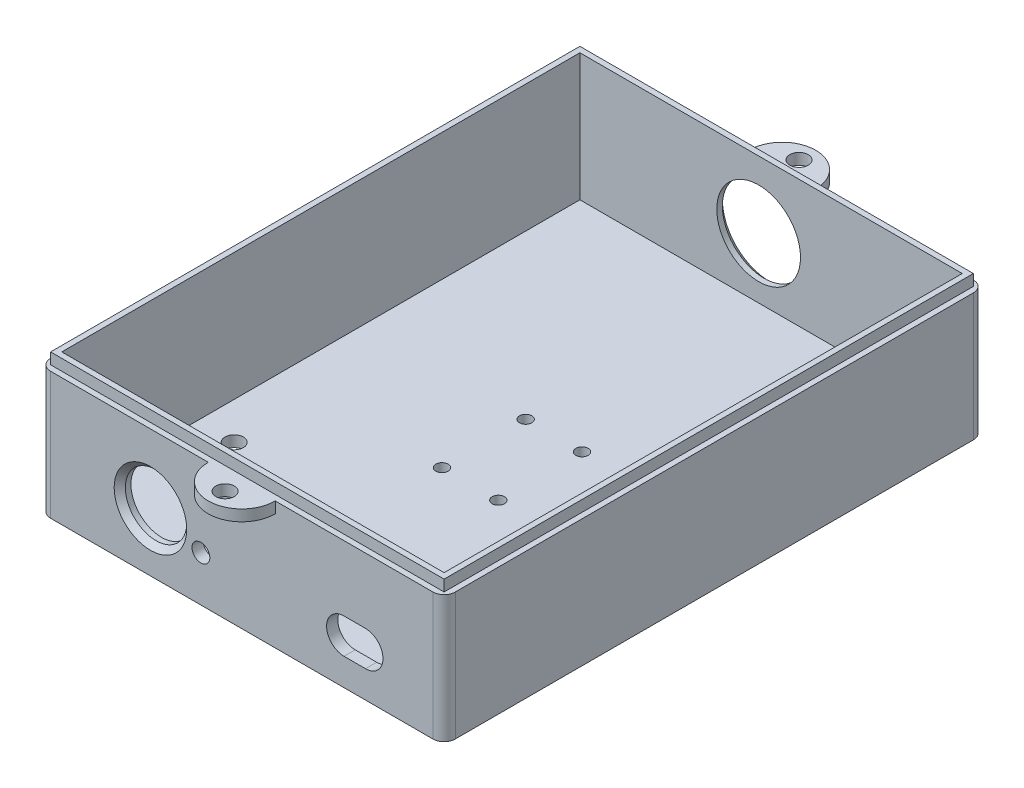
SolidWorks part; units mm, degrees
ref_plane "Front Plane" through (0, 0, 0) normal (1, 0, 0) x (0, 1, 0)
ref_plane "Top Plane" through (0, 0, 0) normal (0, 0, 1) x (0, 1, 0)
ref_plane "Right Plane" through (0, 0, 0) normal (0, 1, 0) x (-1, 0, 0)
sketch "Sketch1" plane through (0, 0, 0) normal (0, 1, 0) x (1, 0, 0)
  line L0 (80.8703, 33.3957) -> (153.3703, 33.3957)
  line L1 (153.3703, 33.3957) -> (153.3703, -63.4327)
  line L2 (153.3703, -63.4327) -> (80.8703, -63.4327)
  line L3 (80.8703, -63.4327) -> (80.8703, 33.3957)
extrude "Boss-Extrude1" add sketch "Sketch1" along normal blind 18 and the other way offset from surface (12.8155 mm away) 0.5 contours L0 L1 L2 L3
shell "Shell1" thickness 2
sketch "Sketch2" plane through (0, 0, -33.3957) normal (0, 0, -1) x (-1, 0, 0)
  line L2 (-80.8703, -12.8155) -> (-153.3703, -12.8155) construction
  line L3 (-153.3703, -12.8155) -> (-153.3703, 18) construction
  circle A0 centre (-114.8937, -0.0005) radius 7.5
  dimension "D1" = 15
  dimension "D2" = 12.815
  dimension "D3" = 38.4765
extrude "Cut-Extrude1" cut sketch "Sketch2" against normal up to surface (2 mm away) up to face at (117.1203, 2.5923, -31.3957)
chamfer "Chamfer1" distance 1 angle 45 1 edges at (107.3937, -0.0005, -33.3957)
sketch "Sketch5" plane through (0, 0, 63.4327) normal (0, 0, 1) x (1, 0, 0)
  line L0 (153.3703, -12.8155) -> (80.8703, -12.8155) construction
  circle A0 centre (100.7621, -2.3405) radius 5.5
  dimension "D1" = 11
  dimension "D2" = 10.475
extrude "Cut-Extrude2" cut sketch "Sketch5" against normal up to surface (2 mm away) up to face at (117.1203, 2.5923, 61.4327)
chamfer "Chamfer2" distance 1 angle 45 1 edges at (106.2621, -2.3405, 63.4327)
sketch "Sketch8" plane through (0, 18, 0) normal (0, 1, 0) x (1, 0, 0)
  line L1 (80.8703, 33.3957) -> (153.3703, 33.3957)
  line L2 (80.8703, 33.3957) -> (80.8703, -63.4327)
  line L3 (80.8703, -63.4327) -> (153.3703, -63.4327)
  line L4 (153.3703, 33.3957) -> (153.3703, -63.4327)
extrude "Cut-Extrude5" cut sketch "Sketch8" against normal blind 8
sketch "Sketch10" plane through (0, 0, 0) normal (0, 1, 0) x (1, 0, 0)
  line L0 (82.8703, 31.3957) -> (151.3703, 31.3957)
  line L1 (151.3703, 31.3957) -> (151.3703, -61.4327)
  line L2 (151.3703, -61.4327) -> (82.8703, -61.4327)
  line L3 (82.8703, -61.4327) -> (82.8703, 31.3957)
  line L4 (81.8703, -62.4327) -> (81.8703, 32.3957)
  line L5 (81.8703, 32.3957) -> (152.3703, 32.3957)
  line L6 (152.3703, 32.3957) -> (152.3703, -62.4327)
  line L7 (152.3703, -62.4327) -> (81.8703, -62.4327)
  dimension "D1" = 1
extrude "Boss-Extrude3" add sketch "Sketch10" along normal blind 2 from surface at 10 starting at face at (117.1203, 10, 15.0185)
sketch "Sketch12" plane through (0, 0, 63.4327) normal (0, 0, 1) x (1, 0, 0)
  circle A0 centre (109.7963, -4.6802) radius 1.6
  dimension "D1" = 3.2
extrude "Cut-Extrude6" cut sketch "Sketch12" against normal up to surface (2 mm away)
fillet "Fillet1" radius 2 4 edges at (80.8703, -1.4077, -33.3957) (80.8703, -1.4077, 63.4327) (153.3703, -1.4077, -33.3957) (153.3703, -1.4077, 63.4327)
sketch "Sketch13" plane through (0, 0, 0) normal (0, 1, 0) x (1, 0, 0)
  line L0 (82.8703, -63.4327) -> (151.3703, -63.4327) construction
  line L1 (111.1203, -63.4327) -> (123.1203, -63.4327)
  circle A0 centre (117.1203, -66.4327) radius 1.65
  arc A1 (111.1203, -63.4327) -> (123.1203, -63.4327) centre (117.1203, -63.4327) ccw
  dimension "D1" = 3.3
extrude "Boss-Extrude4" add sketch "Sketch13" against normal blind 2 from surface at 10 starting at face at (117.1203, 10, 15.0185)
ref_plane "Plane2" through (0, 10, 0) normal (0, 1, 0) x (1, 0, 0)
sketch "Sketch16" plane through (0, 10, 0) normal (0, 1, 0) x (1, 0, 0)
  line L0 (151.3703, 33.3957) -> (82.8703, 33.3957) construction
  line L1 (111.1203, 33.3957) -> (123.1203, 33.3957)
  circle A0 centre (117.1203, 36.3957) radius 1.65
  arc A1 (111.1203, 33.3957) -> (123.1203, 33.3957) centre (117.1203, 33.3957) cw
  arc A2 (123.1203, 33.3957) -> (111.1203, 33.3957) centre (117.1203, 33.3957) ccw construction
extrude "Boss-Extrude5" add sketch "Sketch16" against normal blind 2
sketch "Sketch17" plane through (0, 0, 0) normal (0, 1, 0) x (1, 0, 0)
  circle A0 centre (137.7852, -38.4627) radius 1.65
  circle A1 centre (89.5252, -37.1927) radius 1.65
  dimension "D1" = 3.3
  dimension "D2" = 3.3
extrude "Cut-Extrude8" cut sketch "Sketch17" against normal up to surface (12.8155 mm away) up to face at (117.1203, -12.8155, 15.0185)
sketch "Sketch18" plane through (0, 0, 0) normal (0, 1, 0) x (1, 0, 0)
  line L0 (117.1203, -63.4327) -> (117.1203, 31.3957) construction
  line L1 (151.3703, -63.4327) -> (82.8703, -63.4327) construction
  line L2 (82.8703, 31.3957) -> (151.3703, 31.3957) construction
  line L4 (80.8703, -15.0185) -> (153.3703, -15.0185) construction
  line L5 (80.8703, 33.3957) -> (80.8703, -63.4327) construction
  line L6 (153.3703, 31.3957) -> (153.3703, -61.4327) construction
  circle A0 centre (124.6203, -15.0185) radius 3
  circle A1 centre (109.6203, -15.0185) radius 3
  point P19 (117.1203, -15.0185)
  dimension "D1" = 6
  dimension "D2" = 6
  dimension "D3" = 15
  dimension "D4" = 7.5
ref_plane "Plane1" through (0, 0, 15.0185) normal (0, 0, 1) x (1, 0, 0)
mirror "Mirror1" about plane through (0, 0, 15.0185) normal (0, 0, 1) of "Boss-Extrude4"
sketch "Sketch6" plane through (0, 0, 0) normal (0, 1, 0) x (1, 0, 0)
  circle A0 centre (130.0953, -39.9957) radius 4.75
  circle A1 centre (143.0553, -39.9327) radius 3.5
  circle A2 centre (143.0553, -32.4327) radius 3.5
  dimension "D1" = 7
  dimension "D2" = 7
  dimension "D3" = 9.5
sketch "Sketch20" plane through (0, -12.8155, 0) normal (0, -1, 0) x (1, 0, 0)
  line L0 (151.3703, -31.3957) -> (151.3703, 61.4327) construction
  line L5 (122.1703, 22.5185) -> (112.0703, 7.5185) construction
  line L6 (122.1703, 7.5185) -> (112.0703, 22.5185) construction
  line L7 (82.8703, -31.3957) -> (151.3703, -31.3957) construction
  circle A0 centre (112.0703, 22.5185) radius 1.1
  circle A1 centre (122.1703, 22.5185) radius 1.1
  circle A2 centre (122.1703, 7.5185) radius 1.1
  circle A3 centre (112.0703, 7.5185) radius 1.1
  point P0 (117.1203, 15.0185)
  dimension "D3" = 2.2
  dimension "D4" = 2.2
  dimension "D5" = 2.2
  dimension "D6" = 2.2
  dimension "D1" = 10.1
  dimension "D2" = 10.1
  dimension "D7" = 15
  dimension "D8" = 15
  dimension "D9" = 29.2
  dimension "D10" = 53.9142
extrude "Cut-Extrude9" cut sketch "Sketch20" against normal up to surface (2 mm away) up to face at (137.7852, -10.8155, 36.8127)
sketch "Sketch21" plane through (0, 0, 63.4327) normal (0, 0, 1) x (1, 0, 0)
  line L0 (139.2953, -4.8155) -> (135.4453, -4.8155) construction
  line L1 (139.2953, -7.9405) -> (135.4453, -7.9405)
  line L2 (139.2953, -1.6905) -> (135.4453, -1.6905)
  line L3 (151.3703, -12.8155) -> (151.3703, 10) construction
  line L4 (151.3703, -12.8155) -> (82.8703, -12.8155) construction
  arc A0 (139.2953, -7.9405) -> (139.2953, -1.6905) centre (139.2953, -4.8155) ccw
  arc A1 (135.4453, -1.6905) -> (135.4453, -7.9405) centre (135.4453, -4.8155) ccw
  point P2 (137.3703, -4.8155)
  point P7 (132.3203, -4.8155)
  point P8 (142.4203, -4.8155)
  dimension "D1" = 10.1
  dimension "D2" = 6.25
  dimension "D3" = 14
  dimension "D4" = 8
extrude "Cut-Extrude10" cut sketch "Sketch21" against normal up to surface (2 mm away)
sketch "Sketch23" plane through (0, 0, -33.3957) normal (0, 0, -1) x (1, 0, 0)
  line L0 (141.2453, 6.8155) -> (137.4953, 6.8155) construction
  line L1 (141.2453, 3.6905) -> (137.4953, 3.6905)
  line L2 (141.2453, 9.9405) -> (137.4953, 9.9405)
  line L3 (82.8703, 12.8155) -> (151.3703, 12.8155) construction
  line L4 (151.3703, -10) -> (151.3703, 12.8155) construction
  arc A0 (141.2453, 3.6905) -> (141.2453, 9.9405) centre (141.2453, 6.8155) ccw
  arc A1 (137.4953, 9.9405) -> (137.4953, 3.6905) centre (137.4953, 6.8155) ccw
  point P2 (139.3703, 6.8155)
  point P7 (134.3703, 6.8155)
  point P8 (144.3703, 6.8155)
  dimension "D1" = 10
  dimension "D2" = 6.25
  dimension "D3" = 6
  dimension "D4" = 12
extrude "Cut-Extrude11" cut sketch "Sketch23" against normal up to surface (2 mm away)
